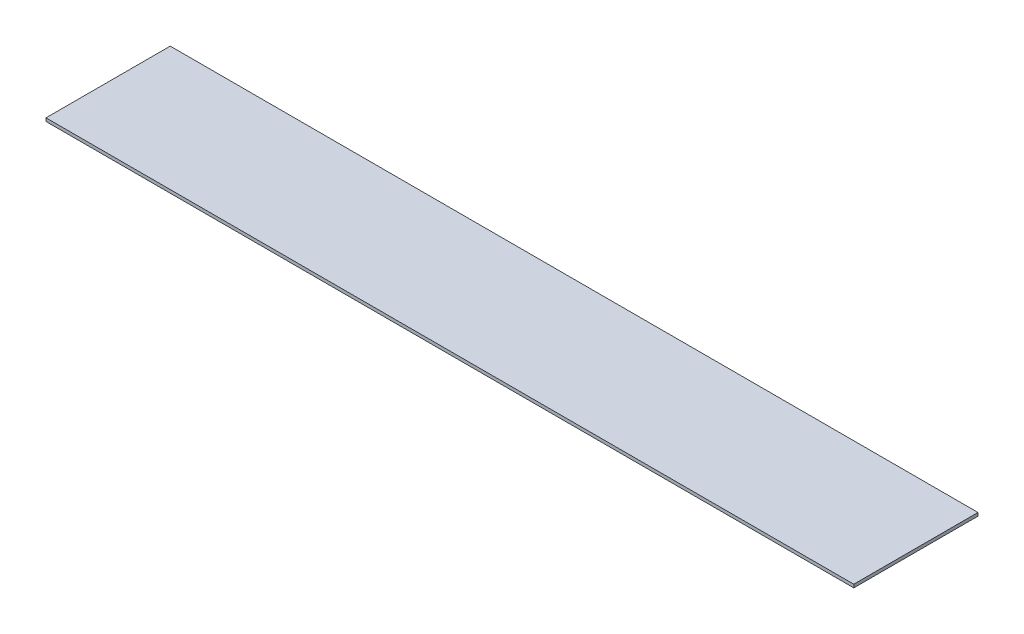
SolidWorks part; units mm, degrees
ref_plane "Front Plane" through (0, 0, 0) normal (0, 0, 1) x (1, 0, 0)
ref_plane "Top Plane" through (0, 0, 0) normal (0, 1, 0) x (1, 0, 0)
ref_plane "Right Plane" through (0, 0, 0) normal (1, 0, 0) x (0, 0, -1)
sketch "Sketch1" plane through (0, 0, 0) normal (0, 1, 0) x (1, 0, 0)
  line L1 (-59.1289, 156.3918) -> (1142.5451, 156.3918)
  line L2 (-59.1289, 156.3918) -> (-59.1289, -28.4005)
  line L3 (-59.1289, -28.4005) -> (1142.5451, -28.4005)
  line L4 (1142.5451, 156.3918) -> (1142.5451, -28.4005)
  dimension "D1" = 1201.674
  dimension "D2" = 184.7924
extrude "Boss-Extrude2" add sketch "Sketch1" along normal blind 4.7625
